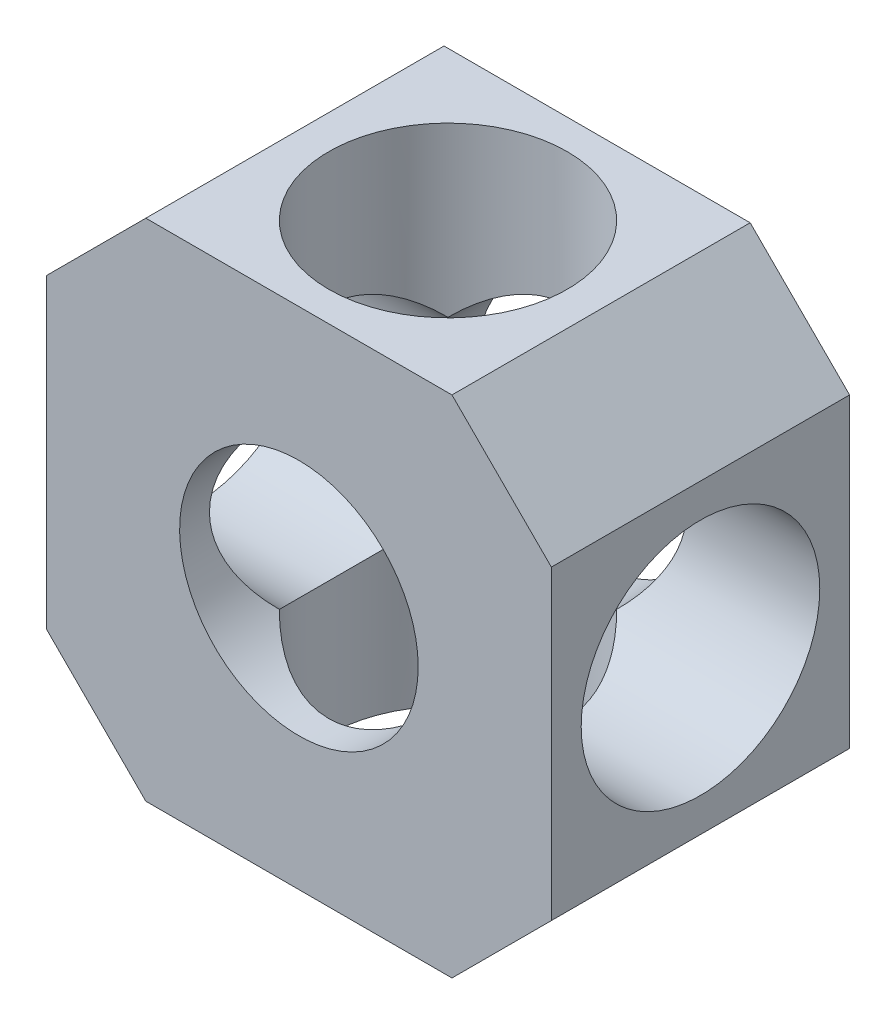
SolidWorks part; units mm, degrees
material "Gray Cast Iron (SN)"
ref_plane "Front Plane" through (0, 0, 0) normal (0, 0, 1) x (1, 0, 0)
ref_plane "Top Plane" through (0, 0, 0) normal (0, 1, 0) x (1, 0, 0)
ref_plane "Right Plane" through (0, 0, 0) normal (1, 0, 0) x (0, 0, -1)
sketch "Sketch2" plane through (0, 0, 0) normal (0, 0, 1) x (1, 0, 0)
  line L0 (-12.7, 7.7) -> (-7.7, 12.7)
  line L1 (-7.7, -12.7) -> (7.7, -12.7)
  line L2 (-12.7, -7.7) -> (-12.7, 7.7)
  line L3 (-7.7, 12.7) -> (7.7, 12.7)
  line L4 (12.7, -7.7) -> (12.7, 7.7)
  line L5 (-12.7, -12.7) -> (12.7, 12.7) construction
  line L6 (-12.7, 12.7) -> (12.7, -12.7) construction
  line L7 (-12.7, -7.7) -> (-7.7, -12.7)
  line L8 (7.7, -12.7) -> (12.7, -7.7)
  line L9 (12.7, 7.7) -> (7.7, 12.7)
  circle A0 centre (0, 0) radius 6
  point P0 (0, 0)
  dimension "D1" = 25.4
  dimension "D2" = 25.4
extrude "Boss-Extrude2" add sketch "Sketch2" along normal blind 15
hole_wizard "Ø12.0 (12) Diameter Hole1" positions "Sketch3" profile "Sketch4" hole size "Ø12.0" standard "ISO"
sketch "Sketch3" plane through (0, 12.7, 0) normal (0, 1, 0) x (1, 0, 0)
  line L0 (-12.7, -15) -> (-12.7, 0) construction
  line L1 (7.7, -15) -> (-7.7, -15) construction
  point P0 (0, -7.5)
  dimension "D1" = 12.7
  dimension "D2" = 7.5
sketch "Sketch4" plane through (0, 12.7, 7.5) normal (1, 0, 0) x (0, 0, 1)
  line L0 (0, 0) -> (0, 33.9252)
  line L1 (0, 33.9252) -> (6, 30.32)
  line L2 (6, 30.32) -> (6, 0)
  line L5 (6, 0) -> (0, 0)
  line L10 (0, 33.9252) -> (-6, 30.32) construction
  line L11 (0, -6.35) -> (0, 107.95) construction
  dimension "Hole Dia." = 12
  dimension "Hole Depth" = 30.32
  dimension "Drill Angle" = 118
pattern_circular "CirPattern1" count 2 every 90 about axis through (0, 0, 0) along (0, 0, 1) of "Ø12.0 (12) Diameter Hole1"
